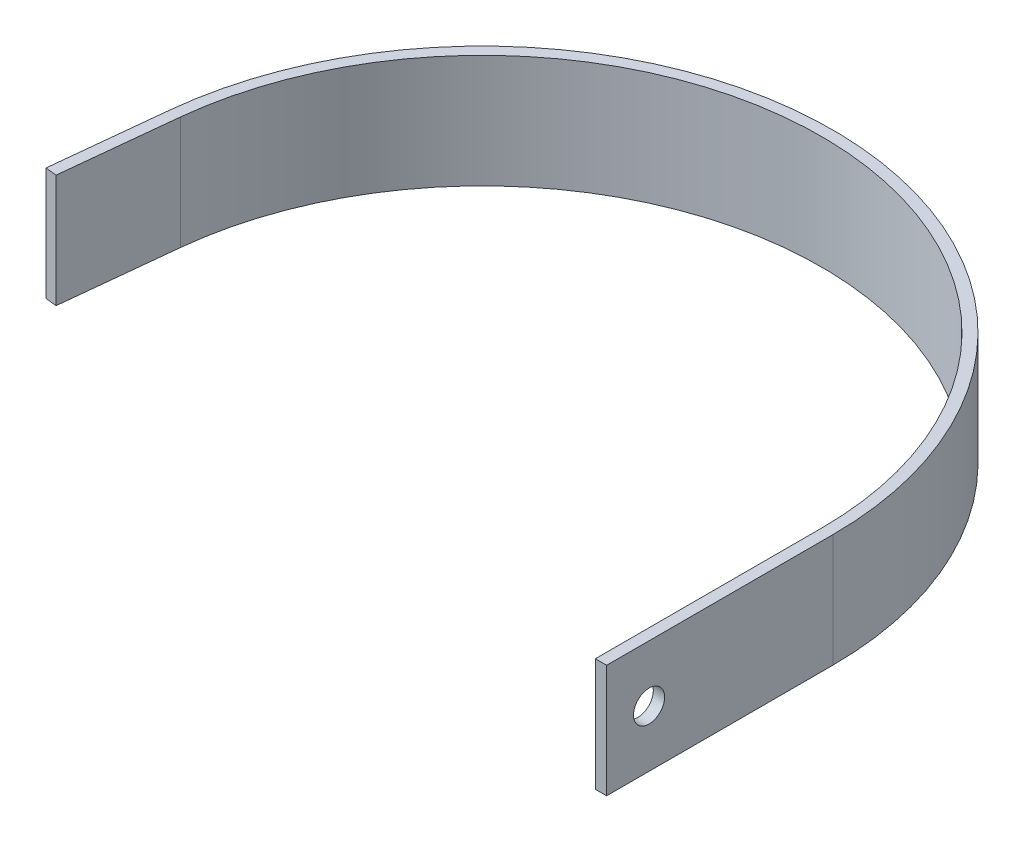
SolidWorks part; units mm, degrees
material "Liga de aço fundido"
ref_plane "Plano frontal" through (0, 0, 0) normal (0, 0, 1) x (1, 0, 0)
ref_plane "Plano superior" through (0, 0, 0) normal (0, 1, 0) x (1, 0, 0)
ref_plane "Plano direito" through (0, 0, 0) normal (1, 0, 0) x (0, 0, -1)
sketch "Esboço1" plane through (0, 0, 0) normal (0, 1, 0) x (1, 0, 0)
  line L0 (-0.5216, 13.9594) -> (-2.6121, -5.931)
  line L1 (119.1497, 7.6877) -> (119.1497, -32.3123)
  line L2 (119.1497, -32.3123) -> (121.1497, -32.3123)
  line L3 (121.1497, -32.3123) -> (121.1497, 7.6877)
  line L4 (-2.6121, -5.931) -> (-4.6012, -5.722)
  line L5 (-4.6012, -5.722) -> (-2.5106, 14.1685)
  arc A0 (-0.5216, 13.9594) -> (119.1497, 7.6877) centre (59.1497, 7.6877) cw
  arc A1 (-2.5106, 14.1685) -> (121.1497, 7.6877) centre (59.1497, 7.6877) cw
  dimension "D2" = 60
  dimension "D1" = 6
  dimension "D3" = 40
  dimension "D4" = 20
  dimension "D5" = 2
  dimension "D6" = 2
extrude "Ressalto-extrusão1" add sketch "Esboço1" along normal blind 20
sketch "Esboço2" plane through (121.1497, 0, 0) normal (1, 0, 0) x (0, 0, -1)
  line L0 (-32.3123, 20) -> (-32.3123, 0) construction
  line L1 (-32.3123, 0) -> (7.6877, 0) construction
  circle A0 centre (-24.8123, 10) radius 2.75
  dimension "D3" = 5.5
  dimension "D1" = 7.5
  dimension "D2" = 10
extrude "Corte-extrusão1" cut sketch "Esboço2" against normal up to surface (2 mm away) up to face at (119.1497, 10, 12.3123)
